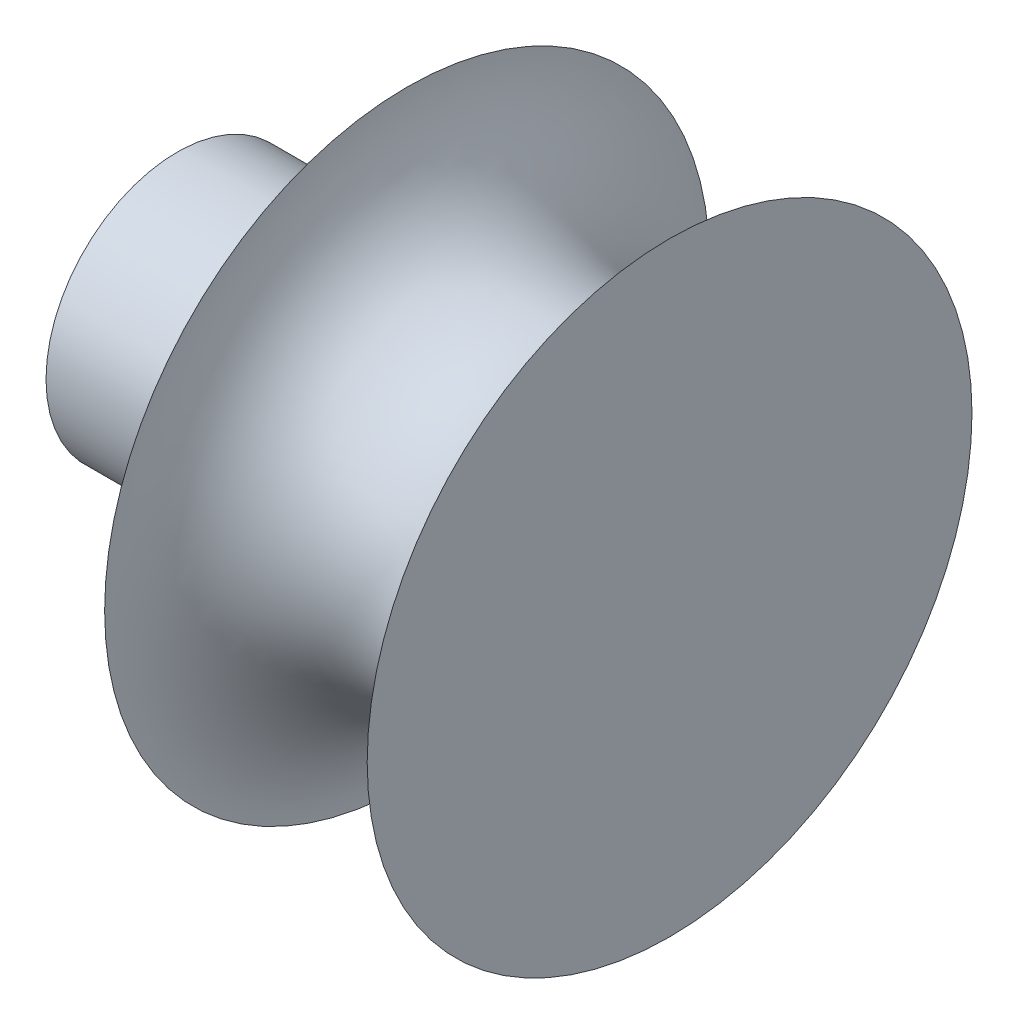
SolidWorks part; units mm, degrees
ref_plane "Front Plane" through (0, 0, 0) normal (0, 0, 1) x (1, 0, 0)
ref_plane "Top Plane" through (0, 0, 0) normal (0, 1, 0) x (1, 0, 0)
ref_plane "Right Plane" through (0, 0, 0) normal (1, 0, 0) x (0, 0, -1)
sketch "Sketch1" plane through (0, 0, 0) normal (0, 0, 1) x (1, 0, 0)
  line L0 (7, 9.2143) -> (7, 4)
  line L1 (0, 0) -> (15, 0)
  line L2 (0, 0) -> (0, 4)
  line L4 (15, 0) -> (15, 9.2143)
  line L5 (0, 4) -> (7, 4)
  arc A0 (7, 9.2143) -> (15, 9.2143) centre (11, 9.2143) ccw
  dimension "D1" = 4
  dimension "D2" = 7
  dimension "D3" = 8
revolve "Revolve1" add sketch "Sketch1" angle 360 about L1
